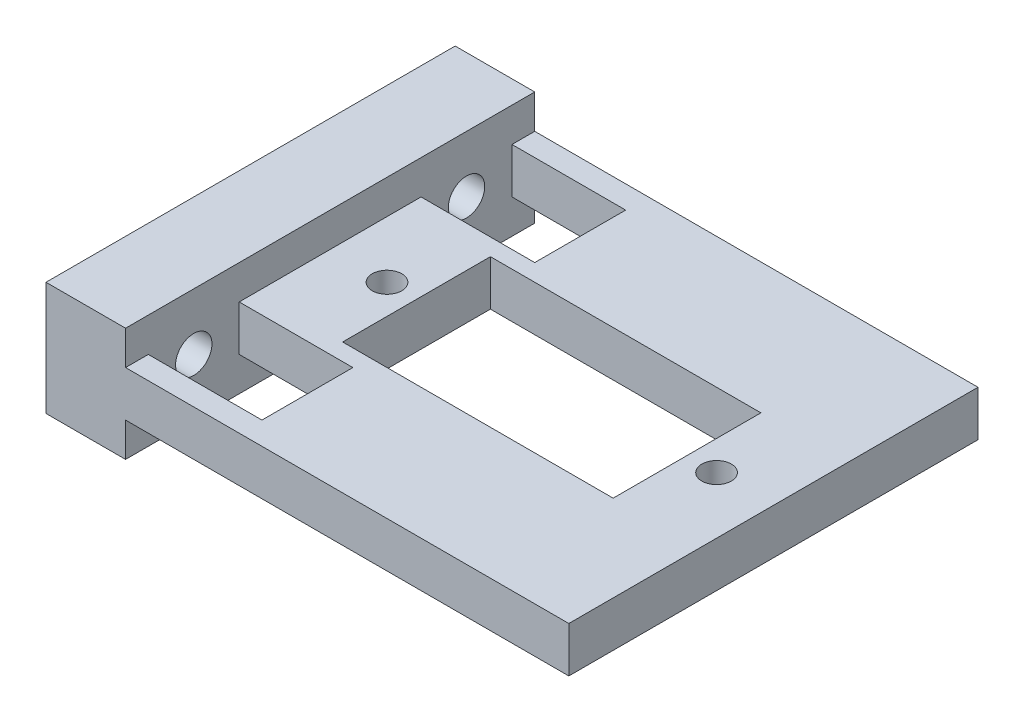
SolidWorks part; units mm, degrees
ref_plane "Front Plane" through (0, 0, 0) normal (0, 0, 1) x (1, 0, 0)
ref_plane "Top Plane" through (0, 0, 0) normal (0, 1, 0) x (1, 0, 0)
ref_plane "Right Plane" through (0, 0, 0) normal (1, 0, 0) x (0, 0, -1)
sketch "Servo_shelf_profile" plane through (0, 0, 0) normal (0, 1, 0) x (1, 0, 0)
  line L1 (-21, -18) -> (25, -18)
  line L2 (-21, -18) -> (-21, 18)
  line L3 (-21, 18) -> (25, 18)
  line L4 (25, -18) -> (25, 18)
  dimension "D1" = 46
  dimension "D2" = 36
extrude "Servo_shelf" add sketch "Servo_shelf_profile" along normal blind 4 from offset 26
sketch "Rear_clamping_block_profile" plane through (0, 0, 0) normal (0, 0, 1) x (1, 0, 0)
  line L1 (-21, 23) -> (-14, 23)
  line L2 (-21, 23) -> (-21, 33)
  line L3 (-21, 33) -> (-14, 33)
  line L4 (-14, 23) -> (-14, 33)
  dimension "D1" = 7
  dimension "D2" = 10
extrude "Rear_clamping_block" add sketch "Rear_clamping_block_profile" along normal blind 36 from offset 18
sketch "Servo_body_window_profile" plane through (0, 0, 0) normal (0, 1, 0) x (1, 0, 0)
  line L1 (-6.4, -6.5) -> (17.4, -6.5)
  line L2 (-6.4, -6.5) -> (-6.4, 6.5)
  line L3 (-6.4, 6.5) -> (17.4, 6.5)
  line L4 (17.4, -6.5) -> (17.4, 6.5)
  dimension "D1" = 23.8
  dimension "D2" = 13
extrude "Servo_body_window" cut sketch "Servo_body_window_profile" along normal through all from offset 25
sketch "Yaw_servo_M2_fasteners_profile" plane through (0, 0, 0) normal (0, 1, 0) x (1, 0, 0)
  circle A0 centre (-9, 0) radius 1.3
  circle A1 centre (20, 0) radius 1.3
  dimension "D1" = 2.6
  dimension "D2" = 2.6
extrude "Yaw_servo_M2_fasteners" cut sketch "Yaw_servo_M2_fasteners_profile" along normal through all from offset 25
sketch "Left_nut_access_profile" plane through (0, 0, 0) normal (0, 1, 0) x (1, 0, 0)
  line L1 (-14, 8) -> (-4, 8)
  line L2 (-14, 8) -> (-14, 16)
  line L3 (-14, 16) -> (-4, 16)
  line L4 (-4, 8) -> (-4, 16)
  dimension "D1" = 10
  dimension "D2" = 8
extrude "Left_nut_access" cut sketch "Left_nut_access_profile" along normal through all from offset 20
sketch "Right_nut_access_profile" plane through (0, 0, 0) normal (0, 1, 0) x (1, 0, 0)
  line L1 (-14, -16) -> (-4, -16)
  line L2 (-14, -16) -> (-14, -8)
  line L3 (-14, -8) -> (-4, -8)
  line L4 (-4, -16) -> (-4, -8)
  dimension "D1" = 10
  dimension "D2" = 8
extrude "Right_nut_access" cut sketch "Right_nut_access_profile" along normal through all from offset 20
sketch "Rear_clamping_M3_profile" plane through (0, 0, 0) normal (1, 0, 0) x (0, 0, -1)
  circle A0 centre (12, 28) radius 1.6
  circle A1 centre (-12, 28) radius 1.6
  dimension "D1" = 3.2
  dimension "D2" = 3.2
extrude "Rear_clamping_M3_holes" cut sketch "Rear_clamping_M3_profile" along normal blind 11 from offset 25
